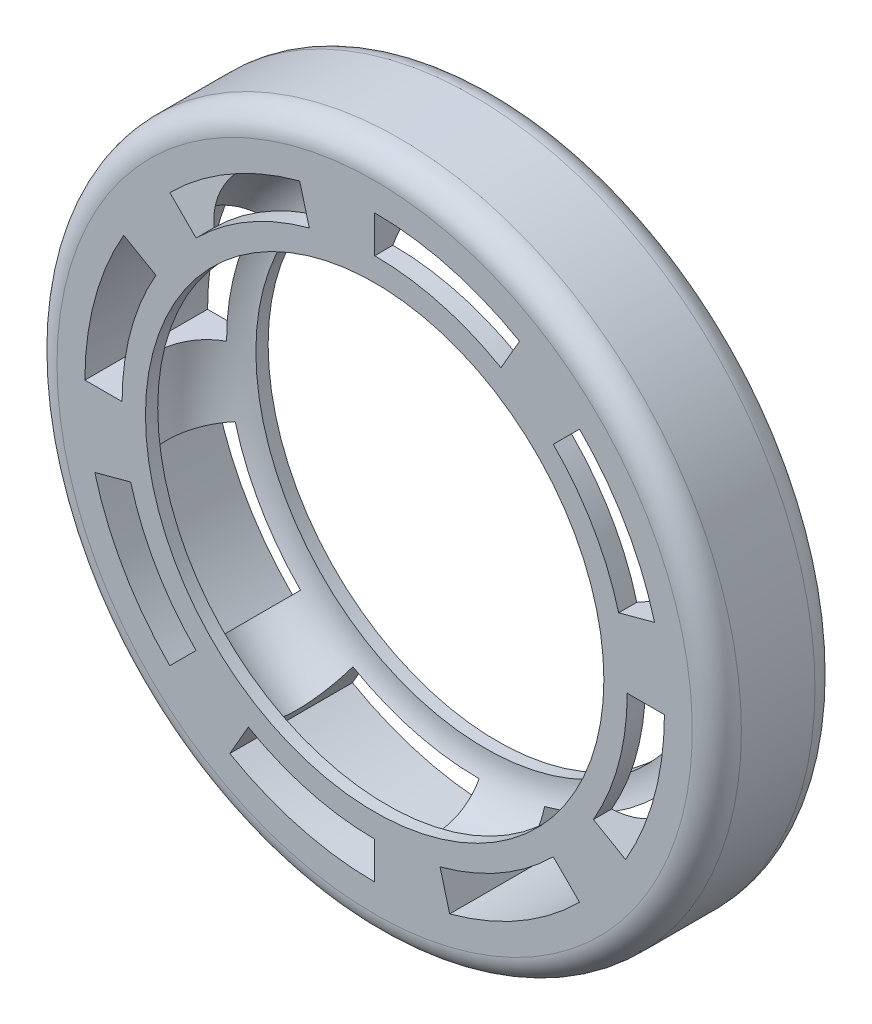
SolidWorks part; units mm, degrees
ref_plane "Front Plane" through (0, 0, 0) normal (0, 0, 1) x (1, 0, 0)
ref_plane "Top Plane" through (0, 0, 0) normal (0, 1, 0) x (1, 0, 0)
ref_plane "Right Plane" through (0, 0, 0) normal (1, 0, 0) x (0, 0, -1)
sketch "Sketch1" plane through (0, 0, 0) normal (0, 1, 0) x (1, 0, 0)
  line L0 (0, 0) -> (30, 0) construction
  line L1 (18.685, -4) -> (18.685, -5)
  line L6 (18.685, 5) -> (27.895, 5)
  line L7 (18.685, 5) -> (18.685, 4)
  line L8 (18.685, -5) -> (27.895, -5)
  line L9 (27.895, 5) -> (27.895, -5)
  line L10 (18.685, 5) -> (27.895, -5) construction
  line L11 (18.685, -5) -> (27.895, 5) construction
  arc A0 (18.685, -4) -> (18.685, 4) centre (18.685, 0) ccw
  point P3 (23.29, 0)
  point P4 (23.29, 0)
ref_axis "Axis3" through (0, 0, -5.5) along (0, 0, 1)
revolve "Revolve1" add sketch "Sketch1" angle 360 about axis through (0, 0, -5.5) along (0, 0, 1)
fillet "Fillet1" radius 2 2 edges at (-27.895, 0, 5) (-27.895, 0, -5)
sketch "Sketch2" plane through (0, 0, 5) normal (0, 0, 1) x (1, 0, 0)
  line L0 (20.59, 0) -> (23.6218, 0)
  line L1 (17.8315, -10.295) -> (20.4571, -11.8109)
  line L2 (14.5594, -14.5594) -> (16.7032, -16.7032)
  line L3 (5.3291, -19.8885) -> (6.1138, -22.8169)
  line L4 (0, -20.59) -> (0, -23.6218)
  line L5 (-10.295, -17.8315) -> (-11.8109, -20.4571)
  line L6 (-14.5594, -14.5594) -> (-16.7032, -16.7032)
  line L7 (-19.8885, -5.3291) -> (-22.8169, -6.1138)
  line L8 (-20.59, 0) -> (-23.6218, 0)
  line L9 (-17.8315, 10.295) -> (-20.4571, 11.8109)
  line L10 (-14.5594, 14.5594) -> (-16.7032, 16.7032)
  line L11 (-5.3291, 19.8885) -> (-6.1138, 22.8169)
  line L12 (0, 20.59) -> (0, 23.6218)
  line L13 (10.295, 17.8315) -> (11.8109, 20.4571)
  line L14 (14.5594, 14.5594) -> (16.7032, 16.7032)
  line L15 (19.8885, 5.3291) -> (22.8169, 6.1138)
  arc A1 (17.8315, -10.295) -> (20.59, 0) centre (0, 0) ccw
  arc A2 (20.4571, -11.8109) -> (23.6218, 0) centre (0, 0) ccw
  arc A3 (6.1138, -22.8169) -> (16.7032, -16.7032) centre (0, 0) ccw
  arc A4 (5.3291, -19.8885) -> (14.5594, -14.5594) centre (0, 0) ccw
  arc A5 (-11.8109, -20.4571) -> (0, -23.6218) centre (0, 0) ccw
  arc A6 (-10.295, -17.8315) -> (0, -20.59) centre (0, 0) ccw
  arc A7 (-22.8169, -6.1138) -> (-16.7032, -16.7032) centre (0, 0) ccw
  arc A8 (-19.8885, -5.3291) -> (-14.5594, -14.5594) centre (0, 0) ccw
  arc A9 (-20.4571, 11.8109) -> (-23.6218, 0) centre (0, 0) ccw
  arc A10 (-17.8315, 10.295) -> (-20.59, 0) centre (0, 0) ccw
  arc A11 (-6.1138, 22.8169) -> (-16.7032, 16.7032) centre (0, 0) ccw
  arc A12 (-5.3291, 19.8885) -> (-14.5594, 14.5594) centre (0, 0) ccw
  arc A13 (11.8109, 20.4571) -> (0, 23.6218) centre (0, 0) ccw
  arc A14 (10.295, 17.8315) -> (0, 20.59) centre (0, 0) ccw
  arc A15 (22.8169, 6.1138) -> (16.7032, 16.7032) centre (0, 0) ccw
  arc A16 (19.8885, 5.3291) -> (14.5594, 14.5594) centre (0, 0) ccw
  point P36 (0, 0)
  dimension "D1" = 8
extrude "Cut-Extrude3" cut sketch "Sketch2" against normal blind 14
